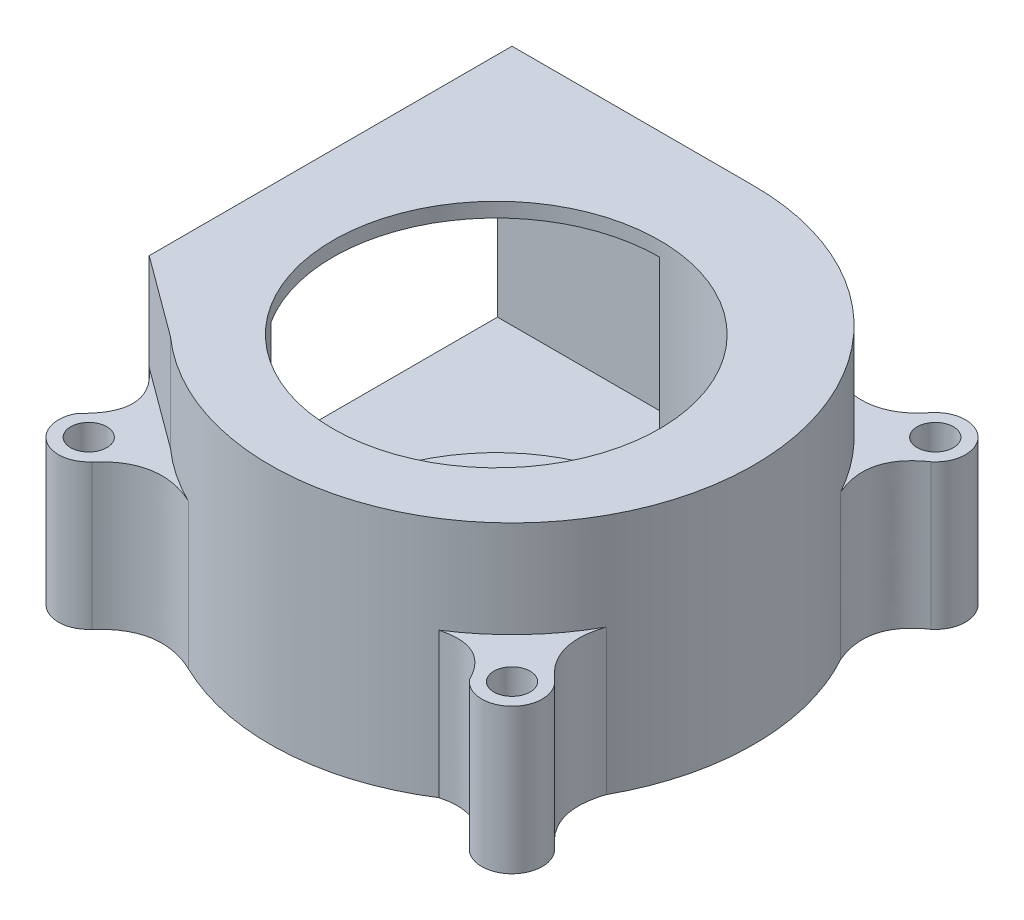
SolidWorks part; units mm, degrees
ref_plane "前视基准面" through (0, 0, 0) normal (0, 0, 1) x (1, 0, 0)
ref_plane "上视基准面" through (0, 0, 0) normal (0, 1, 0) x (1, 0, 0)
ref_plane "右视基准面" through (0, 0, 0) normal (1, 0, 0) x (0, 0, -1)
other "Configuration Table"
sketch "草图1" plane through (0, 0, 0) normal (0, 1, 0) x (1, 0, 0)
  line L1 (0, 0) -> (40, 0)
  line L2 (0, 0) -> (0, 40)
  line L3 (0, 40) -> (40, 40)
  line L4 (40, 0) -> (40, 40)
  circle A0 centre (2.5, 2.5) radius 1.5
  circle A1 centre (37.5, 2.5) radius 1.5
  circle A2 centre (37.5, 37.5) radius 1.5
  circle A4 centre (2.5, 37.5) radius 1.5 [skipped]
  dimension "D3" = 3
  dimension "D4" = 2.5
  dimension "D5" = 2.5
  dimension "D1" = 40
  dimension "D2" = 40
  dimension "D6" = 2
  dimension "D7" = 2
extrude "凸台-拉伸1" add sketch "草图1" along normal blind 20
sketch "草图2" plane through (0, 0, 0) normal (-1, 0, 0) x (0, 0, 1)
  line L0 (-40, 20) -> (-40, 0) construction
  line L1 (-11.5, 1.2) -> (-38.8, 1.2)
  line L2 (-11.5, 1.2) -> (-11.5, 18.8)
  line L3 (-11.5, 18.8) -> (-38.8, 18.8)
  line L4 (-38.8, 1.2) -> (-38.8, 18.8)
  line L5 (-40, 0) -> (0, 0) construction
  line L6 (-40, 20) -> (0, 20) construction
  dimension "D1" = 27.3
  dimension "D2" = 1.2
  dimension "D3" = 1.2
  dimension "D4" = 1.2
extrude "切除-拉伸1" cut sketch "草图2" against normal blind 20
sketch "草图3" plane through (0, 20, 0) normal (0, 1, 0) x (1, 0, 0)
  circle A0 centre (20, 18.7) radius 13.5
  circle A1 centre (2.5, 2.5) radius 1.5 construction
  circle A4 centre (37.5, 2.5) radius 1.5 construction
  dimension "D1" = 17.5
  dimension "D2" = 16.2
  dimension "D3" = 27
extrude "切除-拉伸2" cut sketch "草图3" against normal blind 18
sketch "草图4" plane through (0, 20, 0) normal (0, 1, 0) x (1, 0, 0)
  line L0 (20, 11.5) -> (20, 32.2) construction
  line L1 (20, 40) -> (0, 40)
  line L2 (0, 40) -> (0, 20)
  line L3 (0, 10) -> (6.6926, 5.0697)
  line L4 (0, 40) -> (0, 0) construction
  line L5 (0, 20) -> (0, 10)
  arc A0 (6.6926, 5.0697) -> (20, 40) centre (20, 20) ccw
  dimension "D1" = 30
extrude "切除-拉伸3" cut sketch "草图4" against normal blind 8 flip side to cut
sketch "草图5" plane through (0, 12, 0) normal (0, 1, 0) x (1, 0, 0)
  line L10 (0, 40) -> (0, 10)
  line L11 (20, 40) -> (0, 40)
  line L12 (0, 10) -> (6.6926, 5.0697)
  line L13 (0, 40) -> (0, 10)
  line L14 (20, 40) -> (0, 40)
  arc A0 (39.0764, 35.5597) -> (35.5993, 39.124) centre (37.5, 37.5) ccw
  arc A1 (35.5993, 0.876) -> (39.1801, 4.3513) centre (37.5, 2.5) ccw
  arc A2 (0.3398, 3.7584) -> (4.4007, 0.876) centre (2.5, 2.5) ccw
  arc A6 (37.5, 10.3175) -> (37.5, 29.6825) centre (20, 20) ccw
  arc A7 (6.6926, 5.0697) -> (20, 40) centre (20, 20) ccw
  arc A8 (11.2003, 2.0399) -> (30.7946, 3.1633) centre (20, 20) ccw
  arc A9 (29.6825, 37.5) -> (20, 40) centre (20, 20) ccw
  spline S0 degree 2 poles (0, 10) (3.6388, 6.8784) (0.3398, 3.7584) knots 0 0 0 1 1 1
  spline S1 degree 2 poles (11.2003, 2.0399) (7.1439, 3.9525) (4.4007, 0.876) knots 0 0 0 1 1 1
  spline S2 degree 2 poles (30.7946, 3.1633) (34.0639, 4.0359) (35.5993, 0.876) knots 0 0 0 1 1 1
  spline S3 degree 2 poles (37.5, 10.3175) (36.3198, 6.7657) (39.1801, 4.3513) knots 0 0 0 1 1 1
  spline S4 degree 2 poles (29.6825, 37.5) (33.3343, 36.2155) (35.5993, 39.124) knots 0 0 0 1 1 1
  spline S5 degree 2 poles (37.5, 29.6825) (35.9251, 33.3911) (39.0764, 35.5597) knots 0 0 0 1 1 1
  dimension "D1" = 0
extrude "切除-拉伸4" cut sketch "草图5" against normal through all flip side to cut
sketch "草图6" plane through (0, 2, 0) normal (0, 1, 0) x (1, 0, 0)
  circle A0 centre (20, 18.7) radius 13.5
extrude "凸台-拉伸2" add sketch "草图6" against normal blind 2
